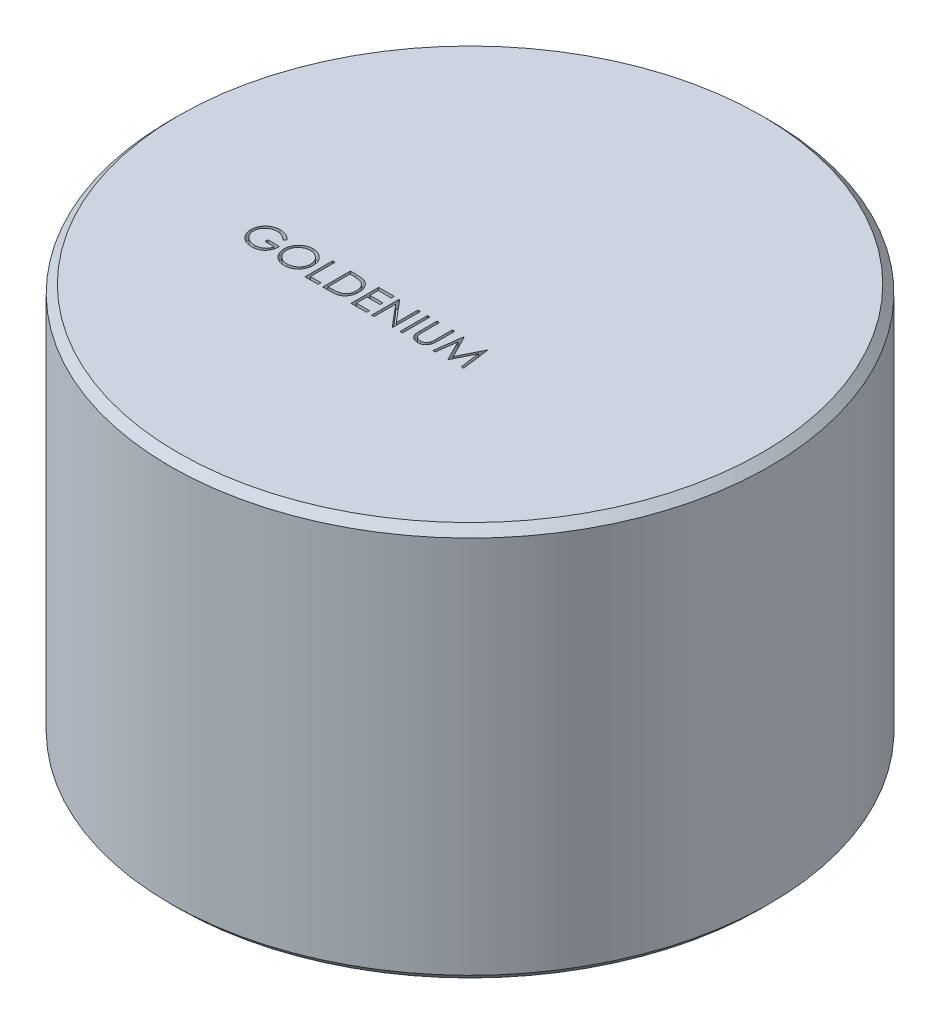
SolidWorks part; units mm, degrees
ref_plane "Plan de face" through (0, 0, 0) normal (0, 0, 1) x (1, 0, 0)
ref_plane "Plan de dessus" through (0, 0, 0) normal (0, 1, 0) x (1, 0, 0)
ref_plane "Plan de droite" through (0, 0, 0) normal (1, 0, 0) x (0, 0, -1)
sketch "Esquisse1" plane through (0, 0, 0) normal (0, 1, 0) x (1, 0, 0)
  circle A0 centre (0, 0) radius 38
  dimension "D1" = 76
extrude "Boss.-Extru.1" add sketch "Esquisse1" along normal blind 50
chamfer "Chanfrein1" distance 1 angle 45 1 edges at (0, 50, 38)
chamfer "Chanfrein2" distance 1 angle 45 1 edges at (0, 0, 38)
sketch "Esquisse2" plane through (0, 50, 0) normal (0, 1, 0) x (1, 0, 0)
  text T0 "GOLDENIUM"
extrude "Enlèv. mat.-Extru.1" cut sketch "Esquisse2" against normal blind 1
sketch "Esquisse3" plane through (0, 0, 0) normal (0, -1, 0) x (1, 0, 0)
  text T0 "GOLDENIUM"
extrude "Enlèv. mat.-Extru.2" cut sketch "Esquisse3" against normal blind 1
